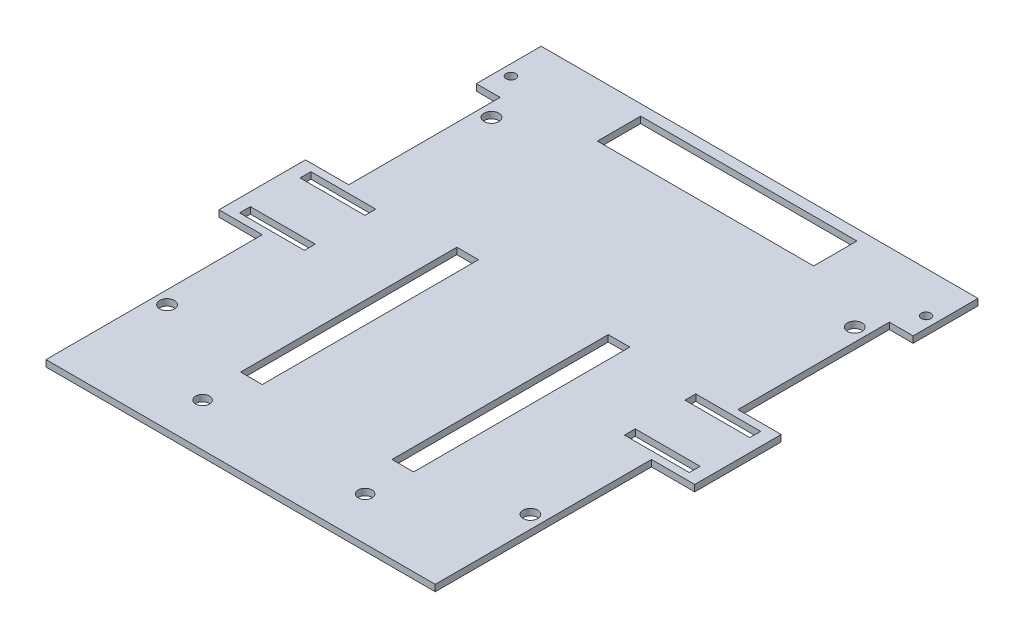
SolidWorks part; units mm, degrees
ref_plane "Front Plane" through (0, 0, 0) normal (0, 0, 1) x (1, 0, 0)
ref_plane "Top Plane" through (0, 0, 0) normal (0, 1, 0) x (1, 0, 0)
ref_plane "Right Plane" through (0, 0, 0) normal (1, 0, 0) x (0, 0, -1)
sketch "Sketch1" plane through (0, 0, 0) normal (0, 1, 0) x (1, 0, 0)
  line L0 (0, 28.7884) -> (0, -31.8108) construction
  line L1 (-43.1329, 0) -> (64.0115, 0) construction
  line L10 (25, 107.5) -> (-25, 107.5)
  line L12 (43.1329, 0) -> (-64.0115, 0) construction
  line L21 (-45, 105) -> (-50.5, 105)
  line L22 (-50.5, 105) -> (-50.5, 120)
  line L33 (-25, 107.5) -> (-25, 117.5)
  line L34 (-25, 117.5) -> (25, 117.5)
  line L35 (25, 117.5) -> (25, 107.5)
  line L36 (-50.5, 120) -> (50.5, 120)
  line L38 (-52, 68.25) -> (-37, 68.25)
  line L39 (-52, 68.25) -> (-52, 65.75)
  line L40 (-52, 65.75) -> (-37, 65.75)
  line L41 (-37, 68.25) -> (-37, 65.75)
  line L42 (-52, 54.25) -> (-37, 54.25)
  line L43 (-52, 54.25) -> (-52, 51.75)
  line L44 (-37, 54.25) -> (-37, 51.75)
  line L45 (-52, 51.75) -> (-37, 51.75)
  line L46 (52, 54.25) -> (52, 51.75)
  line L47 (52, 51.75) -> (37, 51.75)
  line L48 (37, 54.25) -> (37, 51.75)
  line L49 (52, 54.25) -> (37, 54.25)
  line L62 (-45, 105) -> (-45, 70)
  line L63 (-45, 70) -> (-55, 70)
  line L64 (-55, 70) -> (-55, 50)
  line L65 (-55, 50) -> (-45, 50)
  line L66 (-45, 50) -> (-45, 0)
  line L67 (-45, 0) -> (45, 0)
  line L68 (45, 50) -> (45, 0)
  line L69 (55, 50) -> (45, 50)
  line L70 (55, 70) -> (55, 50)
  line L71 (45, 70) -> (55, 70)
  line L72 (45, 105) -> (45, 70)
  line L73 (45, 105) -> (50.5, 105)
  line L74 (50.5, 105) -> (50.5, 120)
  line L75 (20, 20) -> (15, 20)
  line L76 (-20, 70) -> (-15, 70)
  line L77 (-20, 70) -> (-20, 20)
  line L78 (-20, 20) -> (-15, 20)
  line L79 (-15, 70) -> (-15, 20)
  line L80 (15, 70) -> (15, 20)
  line L81 (20, 70) -> (15, 70)
  line L82 (20, 70) -> (20, 20)
  line L83 (52, 65.75) -> (37, 65.75)
  line L84 (37, 68.25) -> (37, 65.75)
  line L85 (52, 68.25) -> (37, 68.25)
  line L86 (52, 68.25) -> (52, 65.75)
  circle A5 centre (48, 110.5) radius 1.1
  circle A6 centre (-48, 110.5) radius 1.1
  circle A19 centre (42, 100) radius 1.7
  circle A20 centre (-42, 100) radius 1.7
  circle A21 centre (-42, 25) radius 1.7
  circle A22 centre (42, 25) radius 1.7
  circle A23 centre (-18.8, 10) radius 1.6
  circle A24 centre (18.8, 10) radius 1.6
  point P52 (0, 0)
  point P61 (50, 70)
  point P62 (-47.75, 105)
  dimension "D7" = 50
  dimension "D15" = 2.5
  dimension "D18" = 20
  dimension "D19" = 90
  dimension "D23" = 3.4
  dimension "D27" = 5
  dimension "D29" = 50
  dimension "D34" = 3.2
  dimension "D22" = 2.2
  dimension "D4" = 101
  dimension "D5" = 11.5
  dimension "D6" = 51.75
  dimension "D8" = 90
  dimension "D9" = 50
  dimension "D10" = 110
  dimension "D11" = 10
  dimension "D12" = 2.5
  dimension "D14" = 96
  dimension "D16" = 15
  dimension "D17" = 3
  dimension "D20" = 2
  dimension "D21" = 10
  dimension "D24" = 42
  dimension "D25" = 18.8
  dimension "D28" = 120
  dimension "D13" = 3
  dimension "D30" = 15
  dimension "D31" = 20
  dimension "D33" = 75
  dimension "D37" = 15
  dimension "D38" = 25
  dimension "D26" = 2
extrude "Boss-Extrude1" add sketch "Sketch1" along normal blind 1.5
